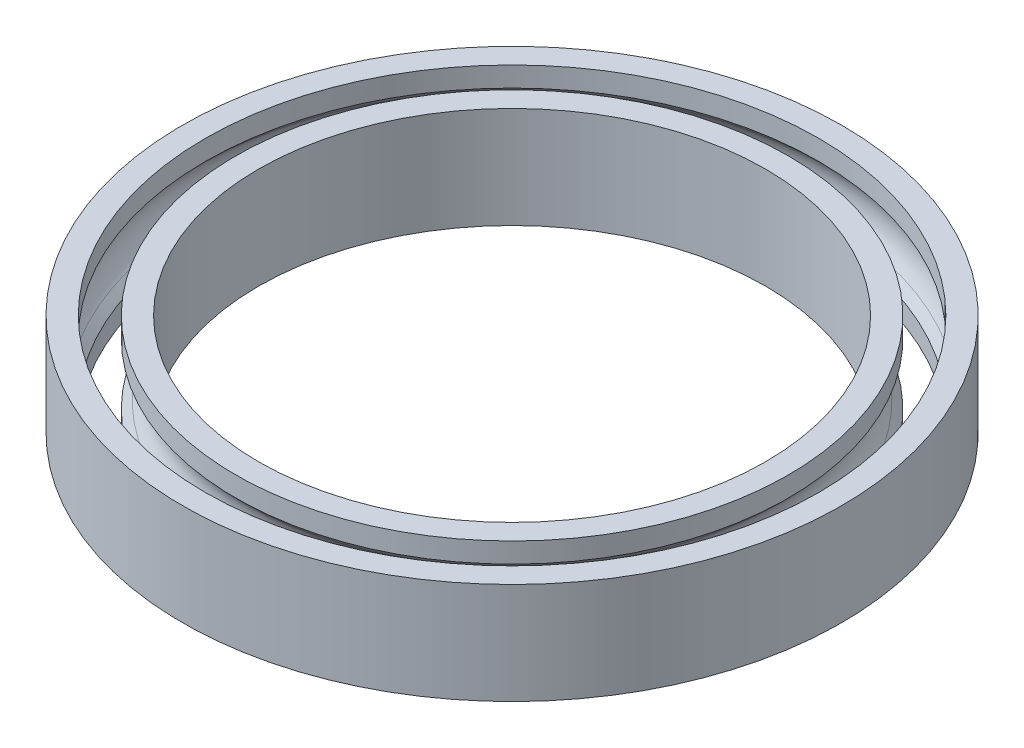
SolidWorks part; units mm, degrees
ref_plane "Front Plane" through (0, 0, 0) normal (0, 0, 1) x (1, 0, 0)
ref_plane "Top Plane" through (0, 0, 0) normal (0, 1, 0) x (1, 0, 0)
ref_plane "Right Plane" through (0, 0, 0) normal (1, 0, 0) x (0, 0, -1)
sketch "Sketch2" plane through (0, 0, 0) normal (0, 0, 1) x (1, 0, 0)
  line L0 (0, 0) -> (0, 40.1762) construction
  line L1 (0, 0) -> (25.55, 0) construction
  line L2 (26.4873, 2.2627) -> (27.25, 3.0255)
  line L3 (27.25, 3.0255) -> (27.25, 5)
  line L4 (27.25, 5) -> (25, 5)
  line L5 (25, 5) -> (25, 0)
  line L6 (25, 0) -> (25.55, 0)
  line L7 (28.75, 10.8619) -> (28.75, 0) construction
  line L8 (30.25, 5) -> (32.5, 5)
  line L9 (30.25, 3.0255) -> (30.25, 5)
  line L10 (31.0127, 2.2627) -> (30.25, 3.0255)
  line L11 (32.5, 5) -> (32.5, 0)
  line L12 (32.5, 0) -> (31.95, 0)
  arc A0 (25.55, 0) -> (26.4873, 2.2627) centre (28.75, 0) cw
  arc A1 (31.95, 0) -> (31.0127, 2.2627) centre (28.75, 0) ccw
  circle A2 centre (28.75, 0) radius 3 construction
  point P3 (26.125, 5)
  dimension "D2" = 3.2
  dimension "D7" = 6
  dimension "D1" = 65
  dimension "D3" = 45
  dimension "D4" = 3
  dimension "D5" = 50
  dimension "D6" = 10
revolve "Revolve1" add sketch "Sketch2" angle 360 about L0
mirror "Mirror1" about plane through (0, 0, 0) normal (0, 1, 0) of bodies 102 103
